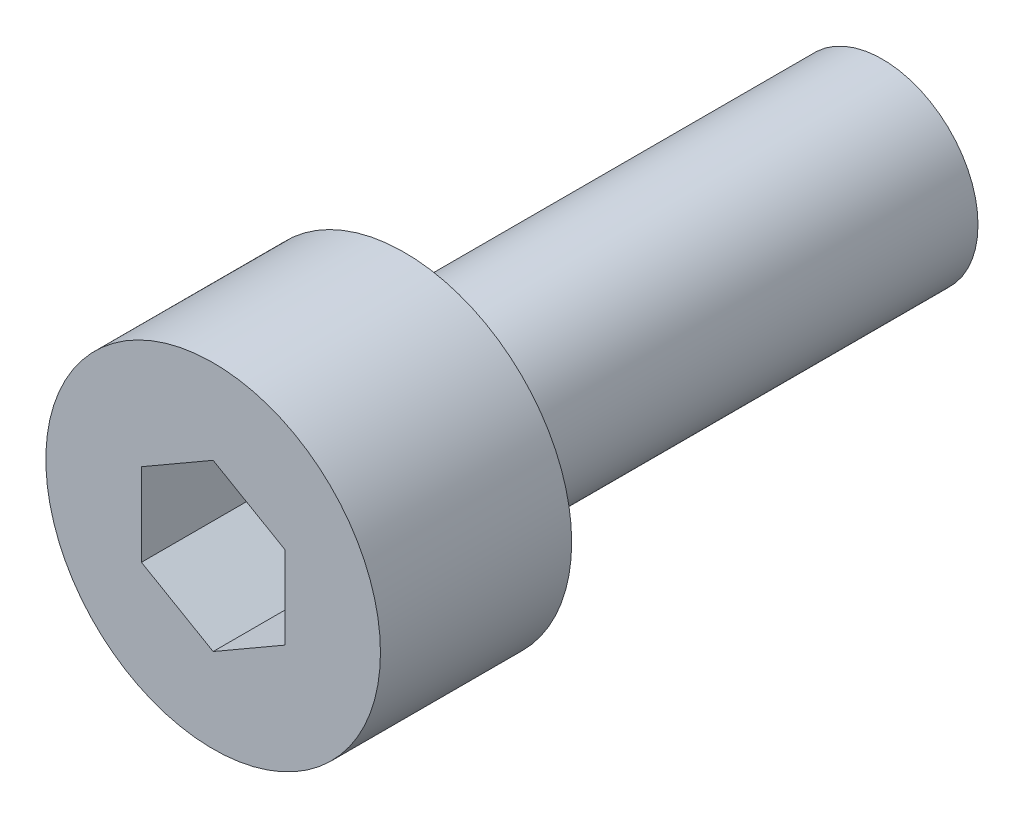
SolidWorks part; units mm, degrees
ref_plane "前视基准面" through (0, 0, 0) normal (0, 0, 1) x (1, 0, 0)
ref_plane "上视基准面" through (0, 0, 0) normal (0, 1, 0) x (1, 0, 0)
ref_plane "右视基准面" through (0, 0, 0) normal (1, 0, 0) x (0, 0, -1)
other "Configuration Table"
sketch "Profile_1" plane through (0, 0, 0) normal (0, 0, 1) x (1, 0, 0)
  circle A0 centre (0, 0) radius 2
extrude "Thread_envelope" add sketch "Profile_1" along normal blind 10 from offset 10
sketch "Profile_2" plane through (0, 0, 0) normal (0, 0, 1) x (1, 0, 0)
  line L0 (1.5, 0.866) -> (0, 1.7321)
  line L1 (0, 1.7321) -> (-1.5, 0.866)
  line L2 (-1.5, 0.866) -> (-1.5, -0.866)
  line L3 (-1.5, -0.866) -> (0, -1.7321)
  line L4 (0, -1.7321) -> (1.5, -0.866)
  line L5 (1.5, -0.866) -> (1.5, 0.866)
  circle A0 centre (0, 0) radius 3.5
extrude "Socket_head" add sketch "Profile_2" along normal blind 4 from offset 0
